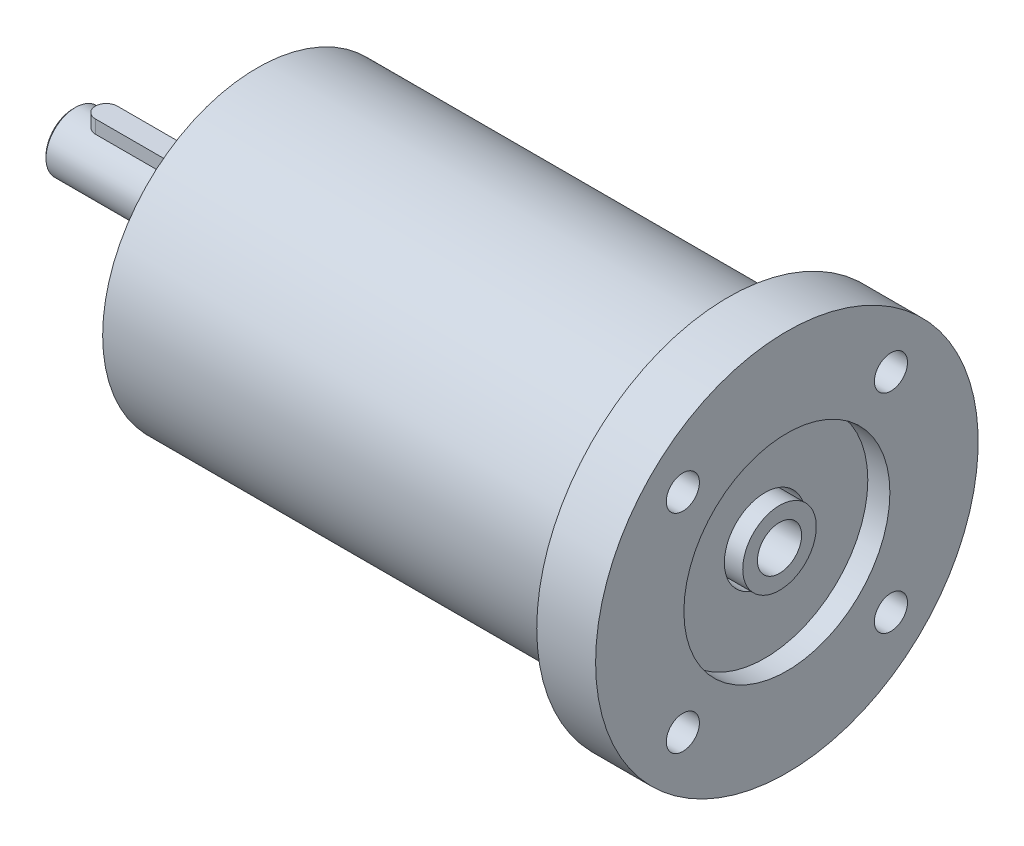
SolidWorks part; units mm, degrees
ref_plane "Přední rovina" through (0, 0, 0) normal (0, 0, 1) x (1, 0, 0)
ref_plane "Horní rovina" through (0, 0, 0) normal (0, 1, 0) x (1, 0, 0)
ref_plane "Pravá rovina" through (0, 0, 0) normal (1, 0, 0) x (0, 0, -1)
sketch "Skica1" plane through (0, 0, 0) normal (0, 0, 1) x (1, 0, 0)
  line L0 (-80.0365, 0) -> (-25, 0) construction
  line L1 (-25, 1.2) -> (-25, 3.7)
  line L2 (-24.7, 4) -> (-2.8, 4)
  line L3 (-2.8, 4) -> (-2.8, 5)
  line L4 (-2.8, 5) -> (-2, 5)
  line L5 (-2, 5) -> (-2, 12.5)
  line L6 (-2, 12.5) -> (0, 12.5)
  line L7 (0, 12.5) -> (0, 21)
  line L8 (0, 21) -> (64, 21)
  line L9 (64, 21) -> (64, 26)
  line L10 (64, 26) -> (72, 26)
  line L11 (72, 26) -> (72, 14)
  line L12 (72, 14) -> (69, 14)
  line L13 (69, 14) -> (69, 5.5)
  line L14 (69, 5.5) -> (38, 5.5)
  line L15 (38, 5.5) -> (38, 0)
  line L16 (-16.3072, 0) -> (5.7602, 0)
  line L17 (-25, 1.2) -> (-17, 1.2)
  line L18 (-17, 1.2) -> (-16.3072, 0)
  line L19 (-16.3072, 0) -> (5.7602, 0) construction
  line L20 (-25, 3.7) -> (-24.7, 4)
  line L21 (5.7602, 0) -> (5.7602, 15.4746)
  line L22 (5.7602, 15.4746) -> (61.2798, 15.4746)
  line L23 (33.5823, 9.0888) -> (33.5823, 0)
  line L24 (33.5823, 0) -> (38, 0)
  line L25 (33.5823, 0) -> (82.0738, 0) construction
  line L26 (33.5823, 9.0888) -> (61.2798, 9.0888)
  line L27 (61.2798, 9.0888) -> (61.2798, 15.4746)
  point P4 (-25, 4)
  dimension "D1" = 22.2
  dimension "D2" = 8
  dimension "D3" = 42
  dimension "D4" = 25
  dimension "D5" = 2
  dimension "D6" = 25
  dimension "D7" = 1
  dimension "D8" = 52
  dimension "D9" = 8
  dimension "D10" = 3
  dimension "D11" = 28
  dimension "D12" = 11
  dimension "D13" = 31
  dimension "D14" = 97
  dimension "D15" = 8
  dimension "D16" = 60
  dimension "D17" = 2.4
revolve "Rotovat1" add sketch "Skica1" angle 360 about L0
sketch "Skica2" plane through (0, 0, 0) normal (0, 0, 1) x (1, 0, 0)
  line L0 (0, 0) -> (110.9362, 0) construction
  line L1 (41, 0) -> (41, 3.5)
  line L2 (41, 3.5) -> (53.5, 3.5)
  line L3 (53.5, 3.5) -> (55, 5)
  line L4 (55, 5) -> (71, 5)
  line L5 (71, 5) -> (71, 3)
  line L6 (71, 3) -> (57, 3)
  line L7 (57, 3) -> (55.2679, 0)
  line L8 (41, 0) -> (55.2679, 0)
  line L10 (72, -26) -> (72, 26) construction
  dimension "D1" = 60
  dimension "D2" = 6
  dimension "D3" = 14
  dimension "D4" = 45
  dimension "D5" = 30
  dimension "D6" = 16
  dimension "D7" = 31
  dimension "D8" = 7
  dimension "D9" = 10
revolve "Rotovat2" add sketch "Skica2" angle 360 about L0
ref_plane "Rovina1" through (-13.75, 4, 0) normal (0, 1, 0) x (0, 0, -1)
sketch "Skica3" plane through (-13.75, 4, 0) normal (0, 1, 0) x (0, 0, -1)
  line L0 (1.5, -6.25) -> (1.5, 6.75)
  line L1 (-1.5, 6.75) -> (-1.5, -6.25)
  line L2 (0, 41.25) -> (0, -68.75) construction
  line L3 (4, 11.25) -> (-4, 11.25) construction
  arc A0 (1.5, 6.75) -> (-1.5, 6.75) centre (0, 6.75) ccw
  arc A1 (-1.5, -6.25) -> (1.5, -6.25) centre (0, -6.25) ccw
  dimension "D2" = 16
  dimension "D3" = 3
  dimension "D1" = 3
extrude "Vysunout1" add sketch "Skica3" along normal blind 1.5 and the other way blind 2 separate body
sketch "Skica4" plane through (0, 0, 0) normal (-1, 0, 0) x (0, 0, 1)
  line L0 (0, 0) -> (11.3137, 11.3137) construction
  line L1 (0, 0) -> (0, 16) construction
  circle A0 centre (11.3137, 11.3137) radius 1.6
  circle A1 centre (0, 0) radius 16 construction
  dimension "D1" = 32
  dimension "D2" = 3.2
  dimension "D3" = 45
extrude "Odebrat vysunutím1" cut sketch "Skica4" against normal blind 10
cosmetic thread "Kosmetický závit1" parameters "D1"=10, "D2"=4
pattern_circular "Kruhové pole1" count 4 over 360 about axis through (0, 0, 0) along (1, 0, 0) of "Odebrat vysunutím1"
sketch "Skica5" plane through (72, 0, 0) normal (1, 0, 0) x (0, 0, -1)
  line L0 (0, 0) -> (14.1421, 14.1421) construction
  line L1 (0, 0) -> (0, 20) construction
  circle A0 centre (0, 0) radius 20 construction
  circle A1 centre (14.1421, 14.1421) radius 2.25
  circle A2 centre (14.1421, -14.1421) radius 2.25
  circle A3 centre (-14.1421, -14.1421) radius 2.25
  circle A4 centre (-14.1421, 14.1421) radius 2.25
  dimension "D1" = 40
  dimension "D3" = 4.5
  dimension "D2" = 45
extrude "Odebrat vysunutím2" cut sketch "Skica5" against normal up to surface (8 mm away) up to face at (64, 0, 21)
move or copy body "Tělo-Přesunout/kopírovat1" [suppressed] bodies to move or copy 102 103 106
